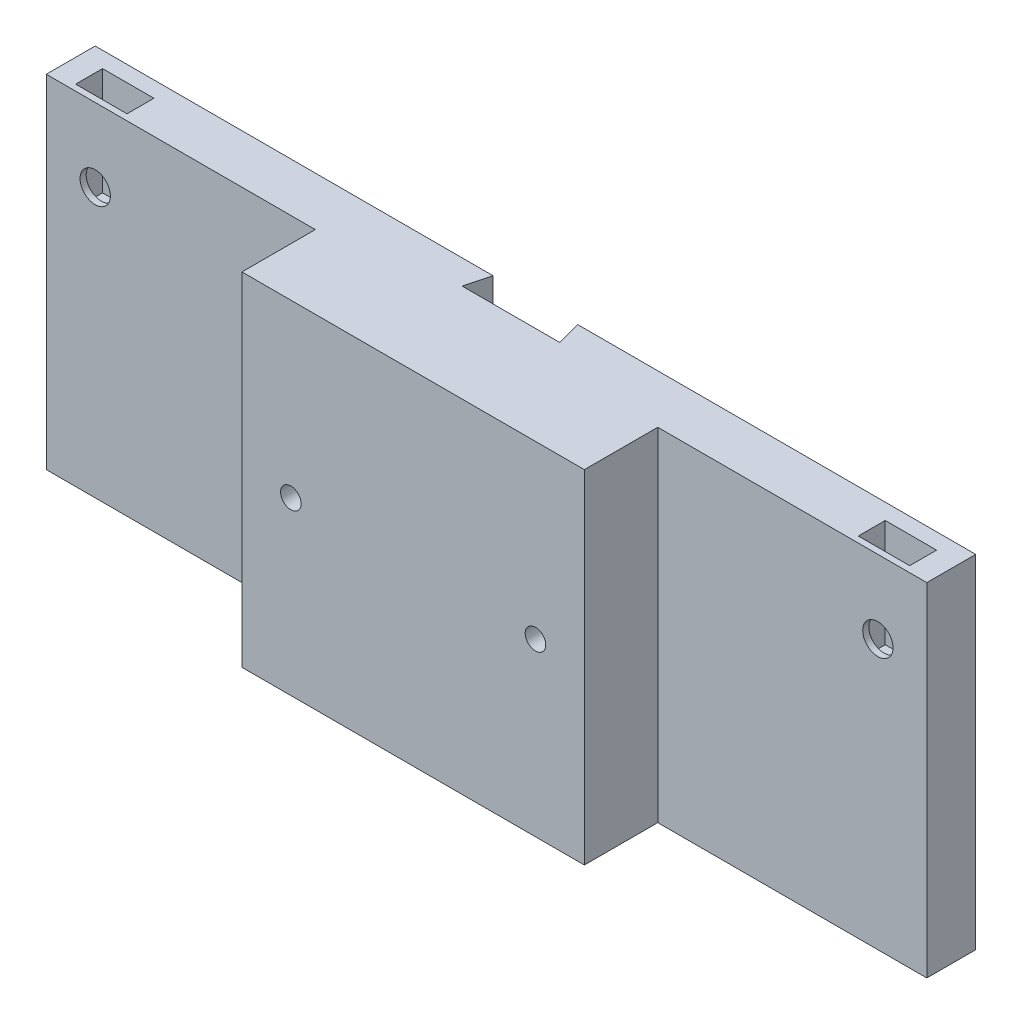
SolidWorks part; units mm, degrees
ref_plane "Ebene vorne" through (0, 0, 0) normal (0, 0, 1) x (1, 0, 0)
ref_plane "Ebene oben" through (0, 0, 0) normal (0, 1, 0) x (1, 0, 0)
ref_plane "Ebene rechts" through (0, 0, 0) normal (1, 0, 0) x (0, 0, -1)
sketch "Skizze1" plane through (0, 0, 0) normal (0, 0, 1) x (1, 0, 0)
  line L0 (0, 52.376) -> (0, -44.6405) construction
  line L1 (-79.8477, 0) -> (80.6647, 0) construction
  line L7 (-90, 35) -> (90, 35)
  line L8 (-90, 35) -> (-90, -35)
  line L9 (-90, -35) -> (90, -35)
  line L10 (90, 35) -> (90, -35)
  circle A0 centre (25, 0) radius 2.1
  circle A3 centre (-25, 0) radius 2.1
  circle A4 centre (80, 20) radius 3.1
  circle A5 centre (-80, 20) radius 3.1
  dimension "D5" = 4.2
  dimension "D8" = 6.2
  dimension "D1" = 180
  dimension "D2" = 70
  dimension "D4" = 25
  dimension "D6" = 20
  dimension "D7" = 80
extrude "Aufsatz-Linear austragen2" add sketch "Skizze1" along normal blind 25
sketch "Skizze4" plane through (0, 0, 25) normal (0, 0, 1) x (1, 0, 0)
  line L0 (0, 47.8661) -> (0, -49.1865) construction
  line L1 (-90, -35) -> (90, -35) construction
  line L2 (90, 35) -> (35, 35)
  line L3 (90, 35) -> (90, -35)
  line L4 (90, -35) -> (35, -35)
  line L5 (35, 35) -> (35, -35)
  line L6 (-90, -35) -> (-35, -35)
  line L7 (-35, 35) -> (-35, -35)
  line L8 (-90, 35) -> (-35, 35)
  line L9 (-90, 35) -> (-90, -35)
  dimension "D1" = 70
extrude "Schnitt-Linear austragen1" cut sketch "Skizze4" against normal blind 15
sketch "Skizze5" plane through (0, 35, 0) normal (0, 1, 0) x (1, 0, 0)
  line L0 (0, 22.4071) -> (0, -47.8593) construction
  line L1 (-56.4007, -6) -> (94.8843, -6) construction
  line L2 (74.75, -3.25) -> (85.25, -3.25)
  line L3 (74.75, -3.25) -> (74.75, -8.75)
  line L4 (74.75, -8.75) -> (85.25, -8.75)
  line L5 (85.25, -3.25) -> (85.25, -8.75)
  line L8 (80, -12.9553) -> (80, -19.1553) construction
  line L9 (-85.25, -3.25) -> (-85.25, -8.75)
  line L10 (-74.75, -8.75) -> (-85.25, -8.75)
  line L11 (-74.75, -3.25) -> (-74.75, -8.75)
  line L12 (-74.75, -3.25) -> (-85.25, -3.25)
  line L13 (90, 0) -> (-90, 0) construction
  dimension "D1" = 10.5
  dimension "D2" = 5.5
  dimension "D3" = 80
  dimension "D4" = 6
extrude "Schnitt-Linear austragen2" cut sketch "Skizze5" against normal blind 22
sketch "Skizze6" plane through (0, 0, 0) normal (0, 0, -1) x (-1, 0, 0)
  line L0 (0, 43.9047) -> (0, -48.9035) construction
  circle A0 centre (-80, 20) radius 6
  circle A1 centre (80, 20) radius 6
  dimension "D1" = 12
extrude "Schnitt-Linear austragen3" cut sketch "Skizze6" against normal blind 2.3
sketch "Skizze7" plane through (0, 35, 0) normal (0, 1, 0) x (1, 0, 0)
  line L0 (0, 40.657) -> (0, -61.9865) construction
  line L1 (8.6603, 0) -> (-8.6603, 0)
  line L2 (90, 0) -> (-90, 0) construction
  line L4 (-8.6603, 0) -> (-10, -5)
  line L5 (-10, -5) -> (10, -5)
  line L6 (8.6603, 0) -> (10, -5)
  point P10 (0, 0)
  point P11 (0, -5)
  dimension "D1" = 10
  dimension "D2" = 5
  dimension "D3" = 75
extrude "Schnitt-Linear austragen4" cut sketch "Skizze7" against normal blind 60
